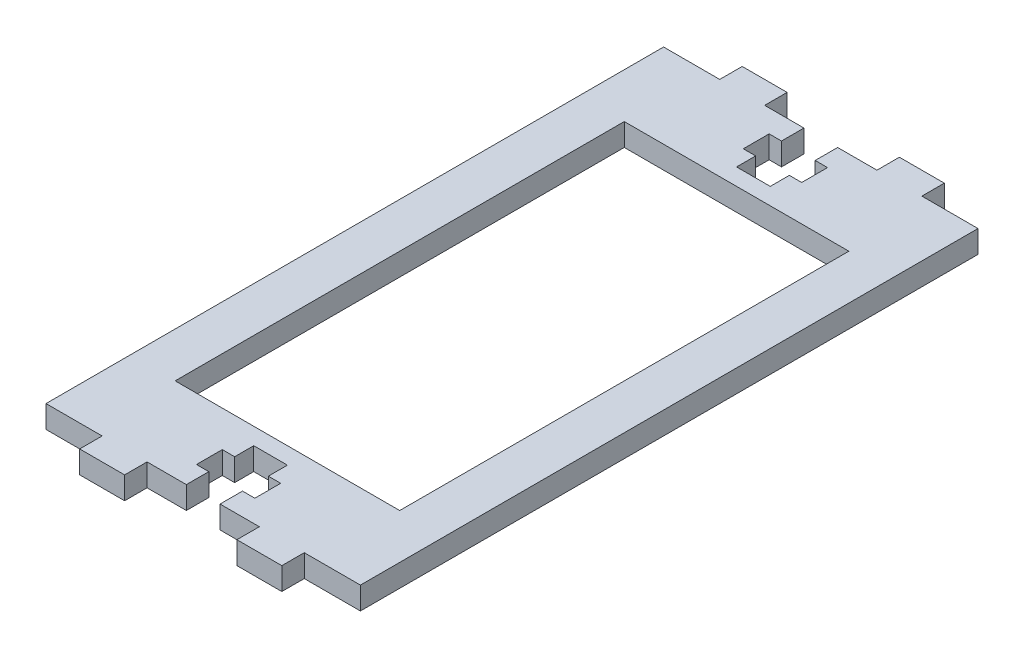
SolidWorks part; units mm, degrees
ref_plane "Front Plane" through (0, 0, 0) normal (0, 0, 1) x (1, 0, 0)
ref_plane "Top Plane" through (0, 0, 0) normal (0, 1, 0) x (1, 0, 0)
ref_plane "Right Plane" through (0, 0, 0) normal (1, 0, 0) x (0, 0, -1)
sketch "Sketch1" plane through (0, 0, 0) normal (0, 1, 0) x (1, 0, 0)
  line L0 (0, 27.2) -> (0, -27.2) construction
  line L1 (-10, -20) -> (10, -20)
  line L2 (-10, -20) -> (-10, 20)
  line L3 (-10, 20) -> (10, 20)
  line L4 (10, -20) -> (10, 20)
  line L5 (-10, -20) -> (10, 20) construction
  line L6 (-10, 20) -> (10, -20) construction
  line L7 (-14, -27.5) -> (-9, -27.5)
  line L8 (-14, -14.5) -> (-14, 14.5)
  line L9 (-14, 27.5) -> (-9, 27.5)
  line L10 (14, -27.5) -> (14, 27.5)
  line L11 (-14, -27.5) -> (14, 27.5) construction
  line L12 (-14, 27.5) -> (14, -27.5) construction
  line L18 (5, 27.5) -> (5, 29.5)
  line L19 (5, 29.5) -> (9, 29.5)
  line L20 (9, 27.5) -> (9, 29.5)
  line L21 (-14, 0) -> (14, 0) construction
  line L22 (9, 27.5) -> (14, 27.5)
  line L23 (-9, 27.5) -> (-9, 29.5)
  line L24 (-5, 29.5) -> (-9, 29.5)
  line L25 (-5, 27.5) -> (-5, 29.5)
  line L26 (-9, -27.5) -> (-9, -29.5)
  line L27 (-5, -29.5) -> (-9, -29.5)
  line L28 (-5, -27.5) -> (-5, -29.5)
  line L29 (9, -27.5) -> (9, -29.5)
  line L30 (5, -27.5) -> (5, -29.5)
  line L31 (5, -29.5) -> (9, -29.5)
  line L32 (-5, -27.5) -> (5, -27.5)
  line L33 (9, -27.5) -> (14, -27.5)
  line L34 (-5, 27.5) -> (5, 27.5)
  line L61 (-14, 14.5) -> (-14, 27.5)
  line L87 (-14, -14.5) -> (-14, -27.5)
  point P0 (0, 0)
  point P6 (0, 0)
  dimension "D1" = 20
  dimension "D2" = 40
  dimension "D3" = 55
  dimension "D4" = 4
  dimension "D5" = 2
  dimension "D6" = 4
  dimension "D7" = 5
extrude "Boss-Extrude1" add sketch "Sketch1" along normal blind 2
sketch "Sketch4" plane through (0, 2, 0) normal (0, 1, 0) x (1, 0, 0)
  line L0 (0, 27.5) -> (0, 20) construction
  line L1 (5, 27.5) -> (-5, 27.5) construction
  line L2 (10, 20) -> (-10, 20) construction
  line L3 (-1.5, 23.2) -> (-2.6, 23.2)
  line L4 (-1.5, 21.5) -> (1.5, 21.5)
  line L5 (-1.5, 21.5) -> (-1.5, 23.2)
  line L6 (-1.5, 27.5) -> (1.5, 27.5)
  line L7 (1.5, 21.5) -> (1.5, 23.2)
  line L8 (-1.5, 21.5) -> (1.5, 27.5) construction
  line L9 (-1.5, 27.5) -> (1.5, 21.5) construction
  line L10 (1.5, 25.5) -> (2.6, 25.5)
  line L12 (1.5, 23.2) -> (2.6, 23.2)
  line L13 (2.6, 25.5) -> (2.6, 23.2)
  line L14 (-2.6, 25.5) -> (-2.6, 23.2)
  line L15 (-1.5, 25.5) -> (-2.6, 25.5)
  line L16 (-1.5, 25.5) -> (-1.5, 27.5)
  line L17 (1.5, 25.5) -> (1.5, 27.5)
  line L18 (14, 0) -> (0, 0) construction
  line L19 (14, -27.5) -> (14, 27.5) construction
  line L20 (1.5, -25.5) -> (1.5, -27.5)
  line L21 (-1.5, -27.5) -> (1.5, -27.5)
  line L22 (-1.5, -25.5) -> (-1.5, -27.5)
  line L23 (-1.5, -25.5) -> (-2.6, -25.5)
  line L24 (-2.6, -25.5) -> (-2.6, -23.2)
  line L25 (-1.5, -23.2) -> (-2.6, -23.2)
  line L26 (-1.5, -21.5) -> (-1.5, -23.2)
  line L27 (-1.5, -21.5) -> (1.5, -21.5)
  line L28 (1.5, -21.5) -> (1.5, -23.2)
  line L29 (1.5, -23.2) -> (2.6, -23.2)
  line L30 (2.6, -25.5) -> (2.6, -23.2)
  line L31 (1.5, -25.5) -> (2.6, -25.5)
  point P6 (0, 24.5)
  point P36 (0, 0)
  dimension "D1" = 3
  dimension "D2" = 6
  dimension "D3" = 2
  dimension "D4" = 2.3
  dimension "D5" = 1.1
extrude "Cut-Extrude2" cut sketch "Sketch4" against normal blind 2
